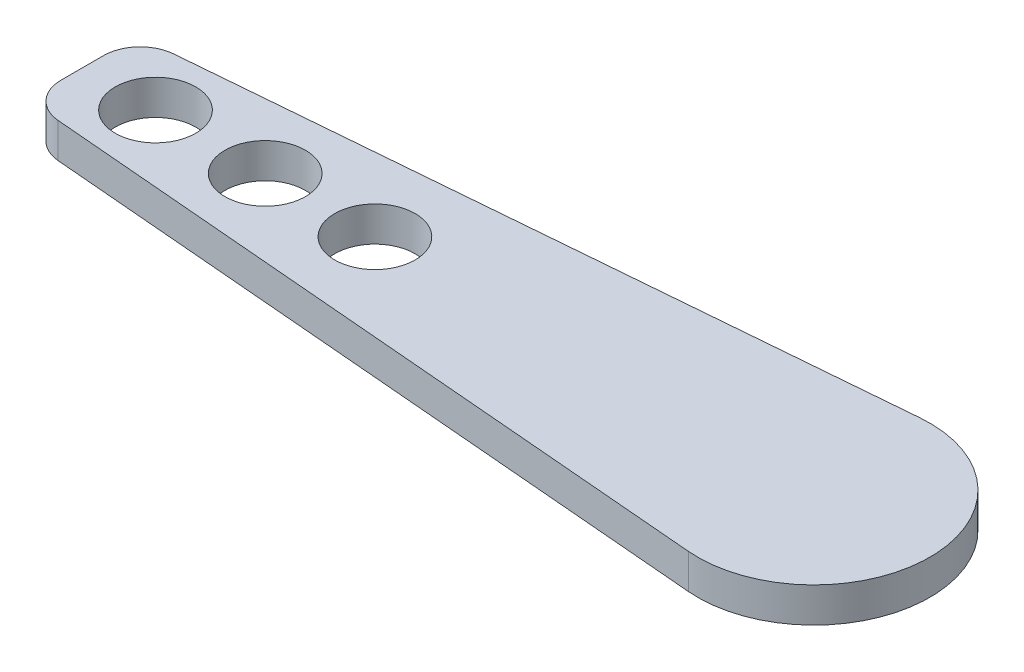
SolidWorks part; units mm, degrees
ref_plane "Front Plane" through (0, 0, 0) normal (0, 0, 1) x (1, 0, 0)
ref_plane "Top Plane" through (0, 0, 0) normal (0, 1, 0) x (1, 0, 0)
ref_plane "Right Plane" through (0, 0, 0) normal (1, 0, 0) x (0, 0, -1)
sketch "Sketch2" plane through (0, 0, 0) normal (0, 1, 0) x (1, 0, 0)
  line L0 (0, 15.9313) -> (-100, 7.5)
  line L1 (-100, -7.5) -> (-100, 7.5)
  line L2 (-100, -7.5) -> (0, -15.9313)
  line L3 (-100, 0) -> (0, 0) construction
  line L4 (-90, 0) -> (-75, 0) construction
  line L5 (-75, 0) -> (-60, 0) construction
  circle A0 centre (0, 0) radius 15.875
  circle A1 centre (-90, 0) radius 5.5
  circle A2 centre (-75, 0) radius 5.5
  circle A3 centre (-60, 0) radius 5.5
  point P8 (-100, 0)
  dimension "D1" = 31.75
  dimension "D3" = 11
  dimension "D2" = 100
  dimension "D4" = 15
  dimension "D5" = 10
  dimension "D6" = 15
extrude "Boss-Extrude1" add sketch "Sketch2" along normal blind 4.7625 contours A0 L0 L1 L2 A3 A2 A1 | A0
fillet "Fillet1" radius 5 2 edges at (-100, 2.3813, -7.5) (-100, 2.3813, 7.5)
equation "\"steeringarmlength\"=100"
equation "\"D2@Sketch2\"=\"steeringarmlength\""
equation "\"mountingholespacing\"=15"
equation "\"D4@Sketch2\"=\"mountingholespacing\""
